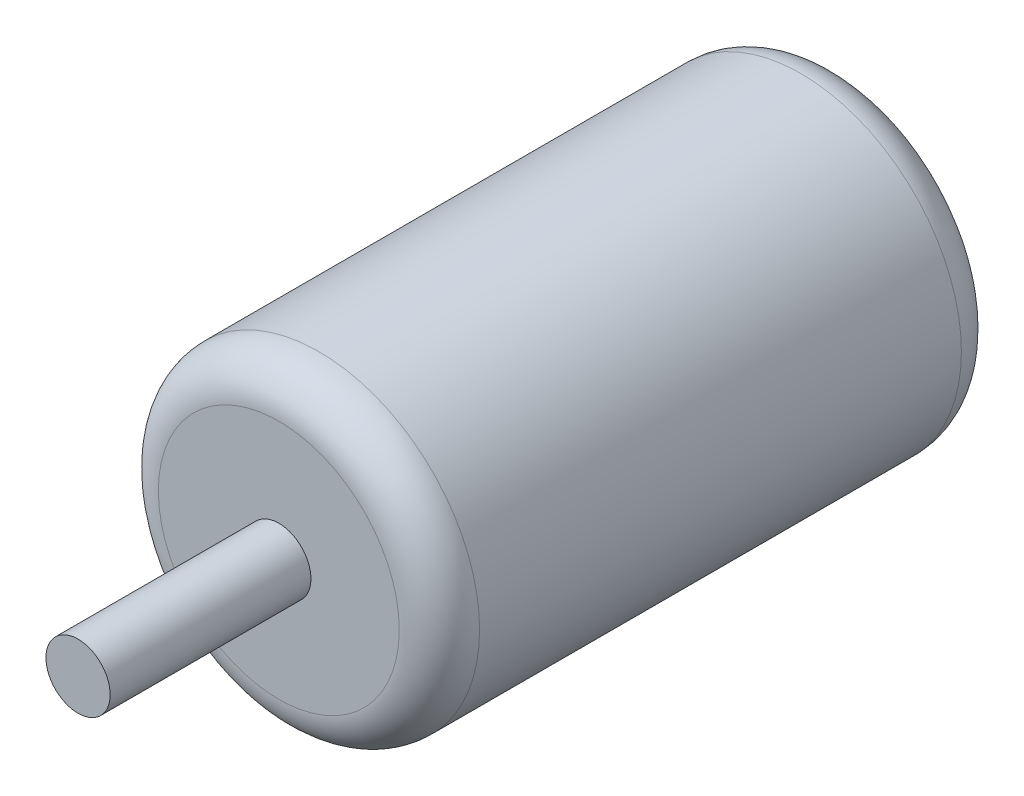
SolidWorks part; units mm, degrees
ref_plane "Front Plane" through (0, 0, 0) normal (0, 0, 1) x (1, 0, 0)
ref_plane "Top Plane" through (0, 0, 0) normal (0, 1, 0) x (1, 0, 0)
ref_plane "Right Plane" through (0, 0, 0) normal (1, 0, 0) x (0, 0, -1)
sketch "Sketch1" plane through (0, 0, 0) normal (0, 0, 1) x (1, 0, 0)
  circle A0 centre (0, 0) radius 20
  dimension "D1" = 40
extrude "Boss-Extrude1" add sketch "Sketch1" along normal blind 70
sketch "Sketch2" plane through (0, 0, 70) normal (0, 0, 1) x (1, 0, 0)
  circle A0 centre (0, 0) radius 4
  dimension "D1" = 8
extrude "Boss-Extrude2" add sketch "Sketch2" along normal blind 25
fillet "Fillet1" radius 5 2 edges at (20, 0, 70) (20, 0, 0)
